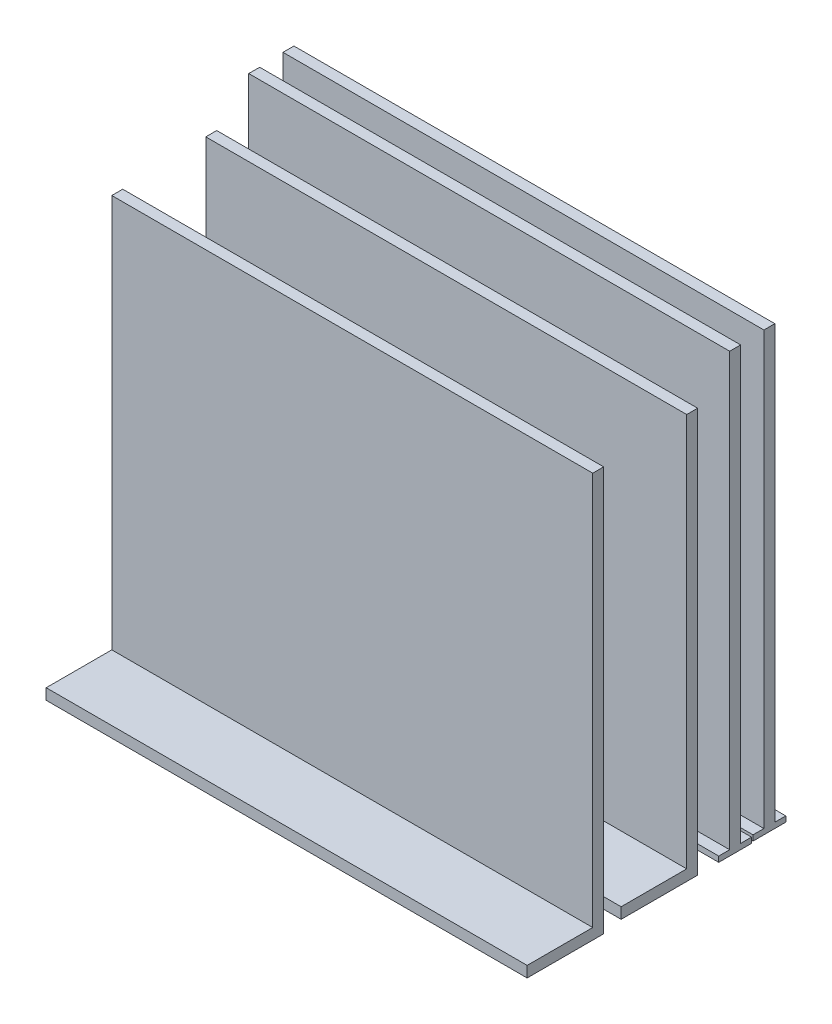
SolidWorks part; units mm, degrees
ref_plane "前视基准面" through (0, 0, 0) normal (0, 0, 1) x (1, 0, 0)
ref_plane "上视基准面" through (0, 0, 0) normal (0, 1, 0) x (1, 0, 0)
ref_plane "右视基准面" through (0, 0, 0) normal (1, 0, 0) x (0, 0, -1)
sketch "草图1" plane through (0, 0, 0) normal (0, 1, 0) x (1, 0, 0)
  line L5 (-110, 2.5) -> (110, 2.5)
  line L6 (-110, 2.5) -> (-110, -2.5)
  line L7 (-110, -2.5) -> (110, -2.5)
  line L8 (110, 2.5) -> (110, -2.5)
  line L9 (-110, 2.5) -> (110, -2.5) construction
  line L10 (-110, -2.5) -> (110, 2.5) construction
  point P0 (0, 0)
  point P1 (0, 0)
  dimension "D1" = 220
  dimension "D2" = 5
extrude "凸台-拉伸1" add sketch "草图1" along normal blind 200
sketch "草图4" plane through (0, 0, 0) normal (0, 1, 0) x (1, 0, 0)
  line L1 (-109.4248, -13.7459) -> (110.5752, -13.7459)
  line L2 (-109.4248, -13.7459) -> (-109.4248, -18.7459)
  line L3 (-109.4248, -18.7459) -> (110.5752, -18.7459)
  line L4 (110.5752, -13.7459) -> (110.5752, -18.7459)
  line L5 (-109.4248, -13.7459) -> (110.5752, -18.7459) construction
  line L6 (-109.4248, -18.7459) -> (110.5752, -13.7459) construction
  point P0 (0.5752, -16.2459)
  dimension "D1" = 220
  dimension "D2" = 5
extrude "凸台-拉伸2" add sketch "草图4" along normal blind 200 separate body
sketch "草图5" plane through (0, 0, 0) normal (0, 1, 0) x (1, 0, 0)
  line L1 (-109.1714, -33.6499) -> (110.8286, -33.6499)
  line L2 (-109.1714, -33.6499) -> (-109.1714, -38.6499)
  line L3 (-109.1714, -38.6499) -> (110.8286, -38.6499)
  line L4 (110.8286, -33.6499) -> (110.8286, -38.6499)
  line L5 (-109.1714, -33.6499) -> (110.8286, -38.6499) construction
  line L6 (-109.1714, -38.6499) -> (110.8286, -33.6499) construction
  point P0 (0.8286, -36.1499)
  dimension "D1" = 220
  dimension "D2" = 5
extrude "凸台-拉伸3" add sketch "草图5" along normal blind 185 separate body
ref_plane "基准面5" through (0, 185, 0) normal (0, 1, 0) x (1, 0, 0)
ref_plane "基准面6" through (-109.1714, 0, 0) normal (-1, 0, 0) x (0, 0, 1)
sketch "草图8" plane through (0, 0, 0) normal (0, 1, 0) x (1, 0, 0)
  line L1 (-107.4373, -78.38) -> (112.5627, -78.38)
  line L2 (-107.4373, -78.38) -> (-107.4373, -83.38)
  line L3 (-107.4373, -83.38) -> (112.5627, -83.38)
  line L4 (112.5627, -78.38) -> (112.5627, -83.38)
  line L5 (-107.4373, -78.38) -> (112.5627, -83.38) construction
  line L6 (-107.4373, -83.38) -> (112.5627, -78.38) construction
  point P0 (2.5627, -80.88)
  dimension "D1" = 220
  dimension "D2" = 5
extrude "凸台-拉伸5" add sketch "草图8" along normal blind 185 separate body
sketch "草图9" plane through (0, 0, 0) normal (0, 1, 0) x (1, 0, 0)
  line L0 (-109.1714, -38.6499) -> (-109.1714, -68.6499)
  line L1 (-109.1714, 2.75) -> (-109.1714, -2.75) construction
  line L2 (-109.1714, -38.6499) -> (110.8286, -38.6499) construction
  line L3 (-109.1714, -68.6499) -> (110.8286, -68.6499)
  line L4 (110.8286, -68.6499) -> (110.8286, -38.6499)
  line L5 (110.8286, -38.6499) -> (-109.1714, -38.6499)
  line L6 (-107.4373, -83.38) -> (-107.4373, -113.38)
  line L7 (-107.4373, -113.38) -> (112.5627, -113.38)
  line L8 (112.5627, -113.38) -> (112.5627, -83.38)
  line L9 (112.5627, -83.38) -> (-107.4373, -83.38)
extrude "凸台-拉伸6" add sketch "草图9" along normal blind 5
sketch "草图12" plane through (0, 0, 0) normal (0, 1, 0) x (1, 0, 0)
  line L0 (-109.4248, -18.7459) -> (-109.4248, -23.7459)
  line L1 (-109.4248, -23.7459) -> (110.5752, -23.7459)
  line L2 (110.5752, -23.7459) -> (110.5752, -18.7459)
  line L3 (110.5752, -18.7459) -> (-109.4248, -18.7459)
  line L4 (-109.4248, -13.7459) -> (-109.4248, -8.7459)
  line L5 (-109.4248, -8.7459) -> (110.5752, -8.7459)
  line L6 (110.5752, -8.7459) -> (110.5752, -13.7459)
  line L7 (110.5752, -13.7459) -> (-109.4248, -13.7459)
  line L10 (-110, -2.5) -> (-110, -7.5)
  line L11 (-110, -7.5) -> (110, -7.5)
  line L12 (110, -7.5) -> (110, -2.5)
  line L13 (110, -2.5) -> (-110, -2.5)
  line L14 (-110, 2.5) -> (-110, 7.5)
  line L15 (-110, 7.5) -> (110, 7.5)
  line L16 (110, 7.5) -> (110, 2.5)
  line L17 (110, 2.5) -> (-110, 2.5)
extrude "凸台-拉伸8" add sketch "草图12" along normal blind 2.5
